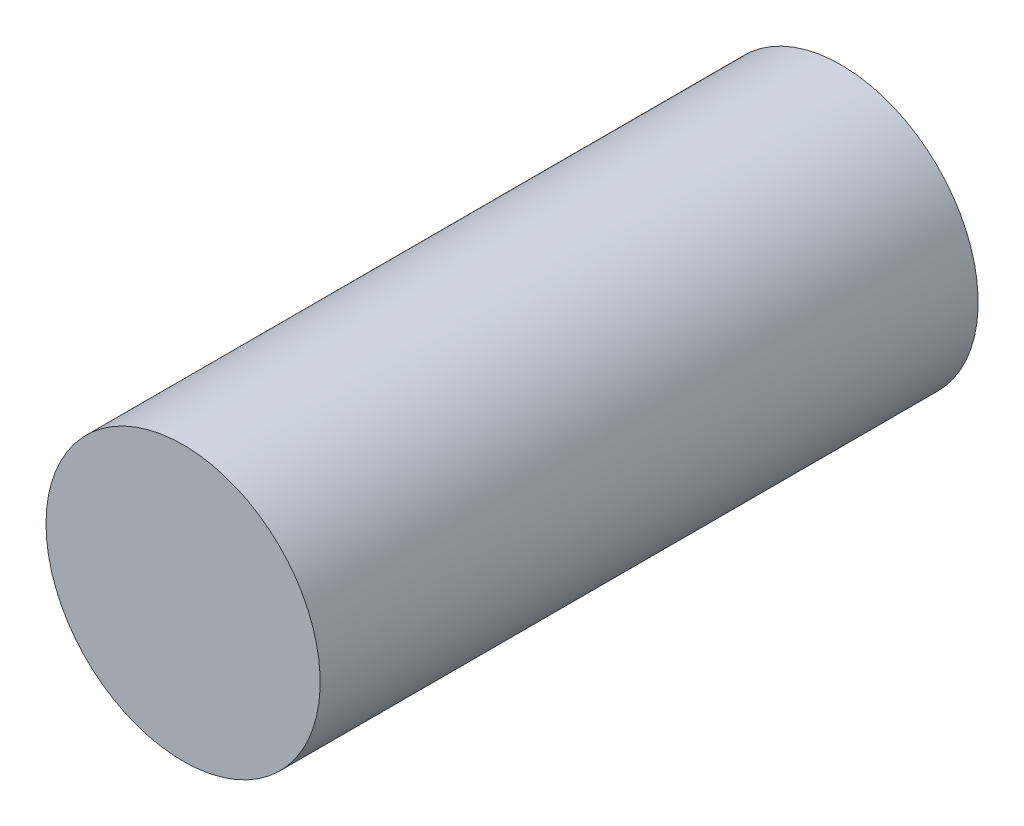
SolidWorks part; units mm, degrees
ref_plane "Front Plane" through (0, 0, 0) normal (0, 0, 1) x (1, 0, 0)
ref_plane "Top Plane" through (0, 0, 0) normal (0, 1, 0) x (1, 0, 0)
ref_plane "Right Plane" through (0, 0, 0) normal (1, 0, 0) x (0, 0, -1)
sketch "Sketch1" plane through (0, 0, 0) normal (0, 0, 1) x (1, 0, 0)
  circle A0 centre (0, 0) radius 63.5
  dimension "D1" = 127
extrude "Boss-Extrude1" add sketch "Sketch1" along normal blind 304.8
